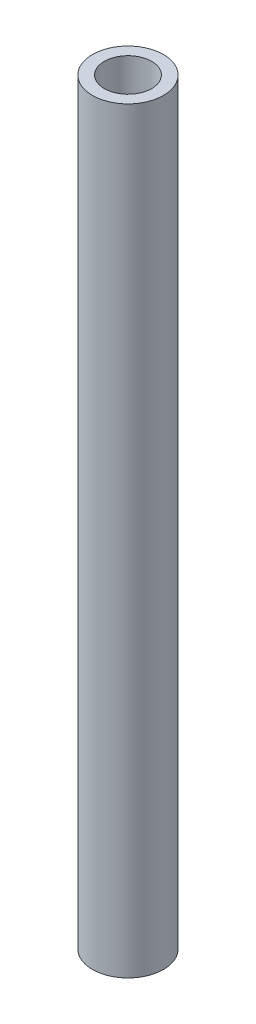
SolidWorks part; units mm, degrees
material "Copper"
ref_plane "Front Plane" through (0, 0, 0) normal (0, 0, 1) x (1, 0, 0)
ref_plane "Top Plane" through (0, 0, 0) normal (0, 1, 0) x (1, 0, 0)
ref_plane "Right Plane" through (0, 0, 0) normal (1, 0, 0) x (0, 0, -1)
sketch "Sketch1" plane through (0, 0, 0) normal (0, 1, 0) x (1, 0, 0)
  circle A0 centre (0, 0) radius 2.3813
  circle A1 centre (0, 0) radius 1.5875
  dimension "D1" = 4.7625
  dimension "D2" = 3.175
extrude "Boss-Extrude1" add sketch "Sketch1" along normal blind 50.8
